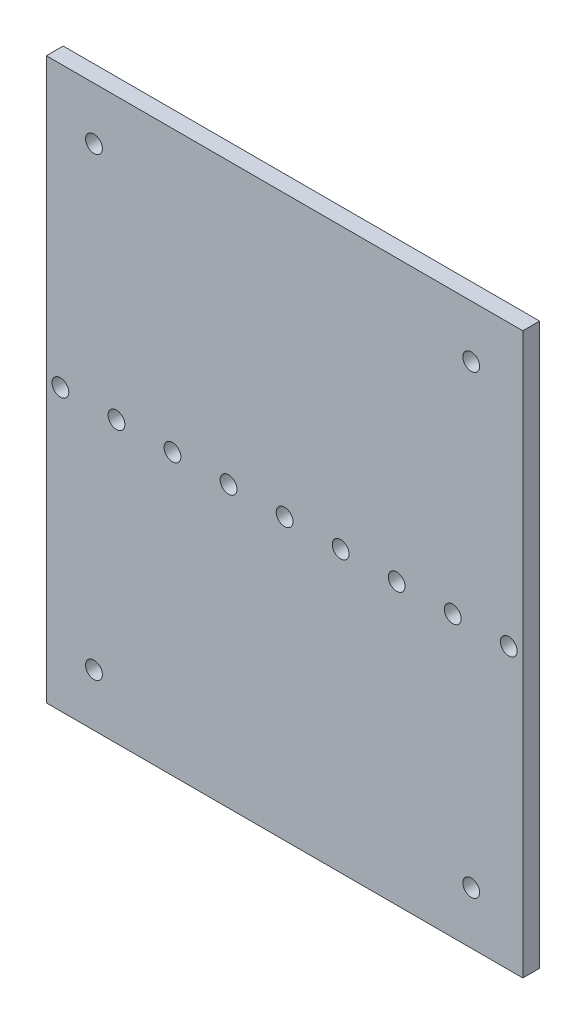
SolidWorks part; units mm, degrees
ref_plane "Front Plane" through (0, 0, 0) normal (0, 0, 1) x (1, 0, 0)
ref_plane "Top Plane" through (0, 0, 0) normal (0, 1, 0) x (1, 0, 0)
ref_plane "Right Plane" through (0, 0, 0) normal (1, 0, 0) x (0, 0, -1)
sketch "Sketch1" plane through (0, 0, 0) normal (0, 0, 1) x (1, 0, 0)
  line L0 (0, 50) -> (0, -50)
  line L1 (0, 50) -> (85, 50)
  line L3 (0, -50) -> (85, -50)
  line L4 (85, 50) -> (85, -50)
  line L5 (-85, 50) -> (85, -50) construction
  line L6 (-85, -50) -> (85, 50) construction
  point P0 (0, 0)
  dimension "D1" = 170
  dimension "D2" = 100
extrude "Boss-Extrude1" add sketch "Sketch1" along normal blind 3
sketch "Sketch2" plane through (0, 0, 3) normal (0, 0, 1) x (1, 0, 0)
  circle A2 centre (75.8, 40.64) radius 1.5
  circle A3 centre (75.8, -40.64) radius 1.5
  circle A9 centre (8.49, 40.64) radius 1.5
  circle A10 centre (8.49, -40.64) radius 1.5
  dimension "D4" = 3
  dimension "D5" = 3
  dimension "D10" = 67.31
  dimension "D8" = 3
  dimension "D12" = 3
extrude "Cut-Extrude1" cut sketch "Sketch2" against normal blind 4
sketch "Sketch3" plane through (0, 0, 3) normal (0, 0, 1) x (1, 0, 0)
  circle A0 centre (42.5, 0) radius 1.5
  circle A1 centre (52.5, 0) radius 1.5
  circle A2 centre (62.5, 0) radius 1.5
  circle A3 centre (72.5, 0) radius 1.5
  circle A4 centre (82.5, 0) radius 1.5
  circle A5 centre (32.5, 0) radius 1.5
  circle A6 centre (22.5, 0) radius 1.5
  circle A7 centre (12.5, 0) radius 1.5
  circle A8 centre (2.5, 0) radius 1.5
  dimension "D1" = 3
  dimension "D2" = 5
extrude "Cut-Extrude2" cut sketch "Sketch3" against normal blind 10
